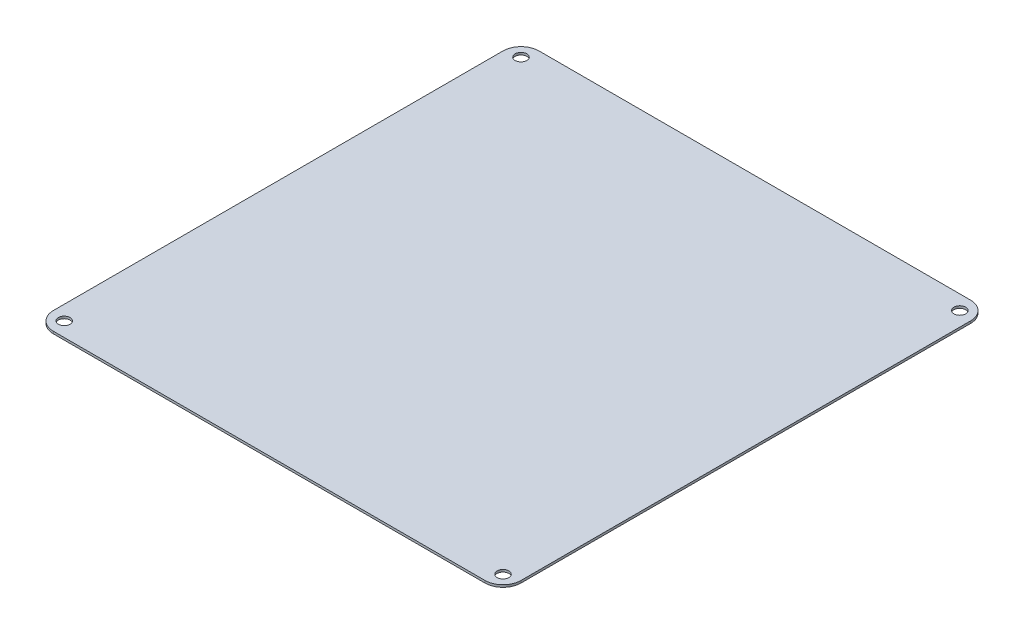
SolidWorks part; units mm, degrees
material "Plain Carbon Steel"
ref_plane "Ground_Plane" through (0, 0, 0) normal (0, 0, 1) x (1, 0, 0)
ref_plane "VehicleCentre_Plane" through (0, 0, 0) normal (0, 1, 0) x (1, 0, 0)
ref_plane "FrontAxle_Plane" through (0, 0, 0) normal (1, 0, 0) x (0, 0, -1)
sketch "Sketch1" plane through (0, 0, 0) normal (0, 1, 0) x (1, 0, 0)
  line L1 (130, -135) -> (-130, -135)
  line L2 (130, -135) -> (130, 135)
  line L3 (130, 135) -> (-130, 135)
  line L4 (-130, -135) -> (-130, 135)
  line L5 (130, -135) -> (-130, 135) construction
  line L6 (130, 135) -> (-130, -135) construction
  point P0 (0, 0)
  dimension "D1" = 270
  dimension "D2" = 260
extrude "Boss-Extrude1" add sketch "Sketch1" along normal blind 1.27
sketch "Sketch2" plane through (0, 1.27, 0) normal (0, 1, 0) x (1, 0, 0)
  line L0 (122, 127) -> (-122, -127) construction
  line L1 (-130, 135) -> (-130, -135) construction
  line L2 (130, 135) -> (-130, 135) construction
  circle A0 centre (-122, 127) radius 3.25
  circle A1 centre (122, 127) radius 3.25
  circle A2 centre (122, -127) radius 3.25
  circle A3 centre (-122, -127) radius 3.25
  point P8 (-129.3915, 114.2331)
  dimension "D1" = 6.5
  dimension "D2" = 8
  dimension "D3" = 8
extrude "Cut-Extrude1" cut sketch "Sketch2" against normal through all
fillet "Fillet1" radius 10 4 edges at (130, 0.635, 135) (-130, 0.635, 135) (130, 0.635, -135) (-130, 0.635, -135)
